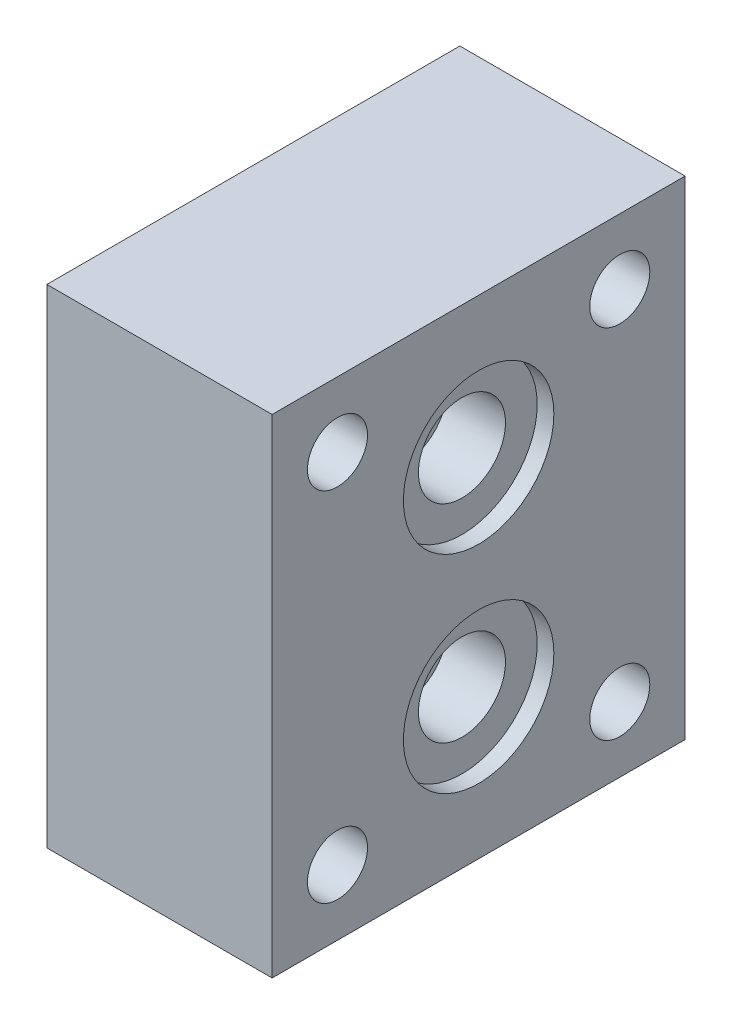
SolidWorks part; units mm, degrees
ref_plane "Front Plane" through (0, 0, 0) normal (1, 0, 0) x (0, 1, 0)
ref_plane "Top Plane" through (0, 0, 0) normal (0, 0, 1) x (0, 1, 0)
ref_plane "Right Plane" through (0, 0, 0) normal (0, 1, 0) x (-1, 0, 0)
sketch "Sketch1" plane through (0, 0, 0) normal (1, 0, 0) x (0, 1, 0)
  line L1 (0, 0) -> (82.55, 0)
  line L2 (0, 0) -> (0, 69.85)
  line L3 (0, 69.85) -> (82.55, 69.85)
  line L4 (82.55, 0) -> (82.55, 69.85)
extrude "Boss-Extrude1" add sketch "Sketch1" along normal blind 38.1
sketch "Sketch2" plane through (0, 0, 0) normal (1, 0, 0) x (0, 1, 0)
  circle A0 centre (11.049, 11.049) radius 5.08
extrude "Cut-Extrude2" cut sketch "Sketch2" against normal through all from offset 38.1
sketch "Sketch3" plane through (0, 0, 0) normal (1, 0, 0) x (0, 1, 0)
  circle A0 centre (71.501, 11.049) radius 5.08
  circle A1 centre (11.049, 58.801) radius 5.08
  circle A2 centre (71.501, 58.801) radius 5.08
extrude "Cut-Extrude4" cut sketch "Sketch3" against normal through all from offset 38.1
sketch "Sketch4" plane through (0, 0, 0) normal (1, 0, 0) x (0, 1, 0)
  circle A0 centre (23.749, 34.925) radius 7.366
extrude "Cut-Extrude6" cut sketch "Sketch4" against normal blind 12.7 from offset 38.1
sketch "Sketch5" plane through (0, 0, 0) normal (1, 0, 0) x (0, 1, 0)
  circle A0 centre (23.749, 34.925) radius 12.7254
extrude "Cut-Extrude8" cut sketch "Sketch5" against normal blind 2.8194 from offset 38.1
sketch "Sketch6" plane through (0, 0, 0) normal (1, 0, 0) x (0, 1, 0)
  circle A0 centre (58.801, 34.925) radius 7.366
extrude "Cut-Extrude10" cut sketch "Sketch6" against normal blind 12.7 from offset 38.1
sketch "Sketch7" plane through (0, 0, 0) normal (1, 0, 0) x (0, 1, 0)
  circle A0 centre (58.801, 34.925) radius 12.7254
extrude "Cut-Extrude12" cut sketch "Sketch7" against normal blind 2.8194 from offset 38.1
